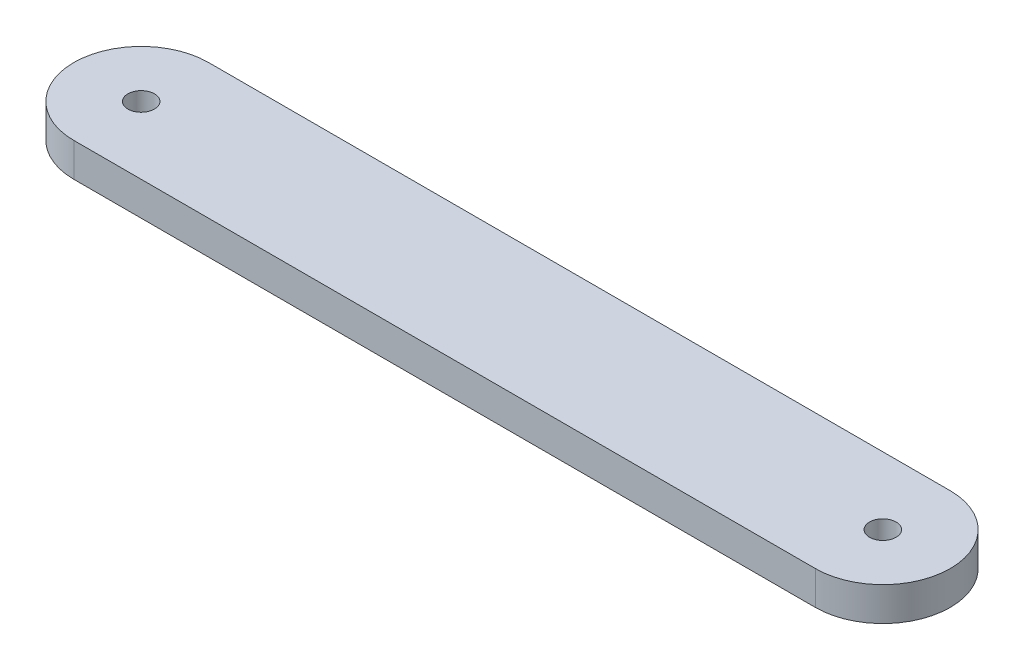
SolidWorks part; units mm, degrees
ref_plane "Front Plane" through (0, 0, 0) normal (0, 0, 1) x (1, 0, 0)
ref_plane "Top Plane" through (0, 0, 0) normal (0, 1, 0) x (1, 0, 0)
ref_plane "Right Plane" through (0, 0, 0) normal (1, 0, 0) x (0, 0, -1)
sketch "Sketch1" plane through (0, 0, 0) normal (0, 1, 0) x (1, 0, 0)
  line L0 (0, 0) -> (139.7, 0) construction
  line L1 (0, 12.7) -> (139.7, 12.7)
  line L2 (0, -12.7) -> (139.7, -12.7)
  arc A0 (0, 12.7) -> (0, -12.7) centre (0, 0) ccw
  arc A1 (139.7, -12.7) -> (139.7, 12.7) centre (139.7, 0) ccw
  point P3 (69.85, 0)
  point P8 (139.7, 0)
  point P9 (0, 0)
  dimension "D2" = 12.7
  dimension "D1" = 139.7
extrude "Boss-Extrude1" add sketch "Sketch1" along normal blind 6.35
sketch "Sketch3" plane through (0, 6.35, 0) normal (0, 1, 0) x (1, 0, 0)
  circle A0 centre (0, 0) radius 2.5
  dimension "D1" = 5
extrude "Cut-Extrude1" cut sketch "Sketch3" against normal blind 6.35
pattern_linear "LPattern1" count 2 spacing 139.7 along (1, 0, 0) of "Cut-Extrude1"
